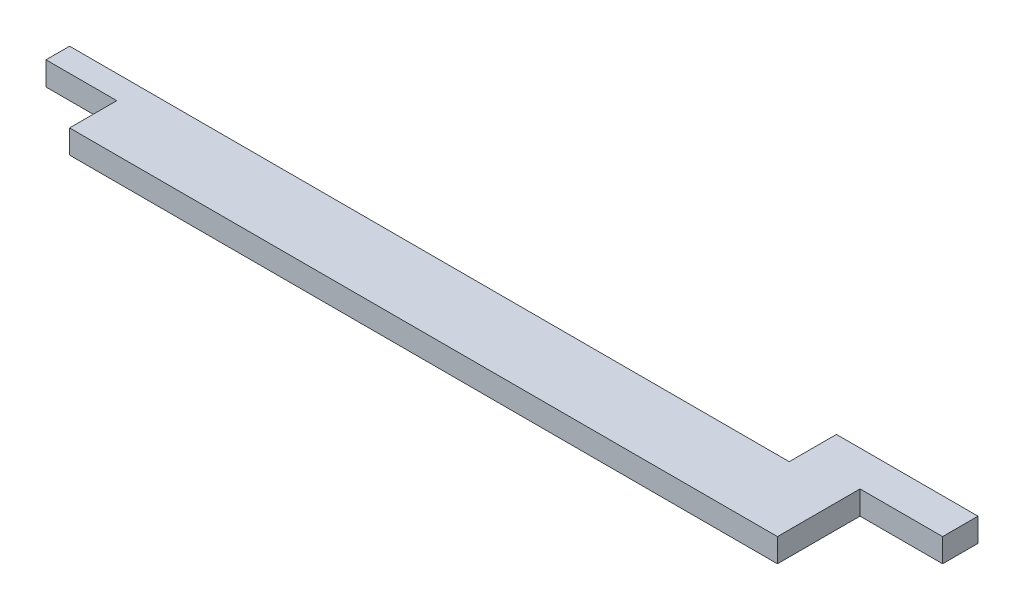
SolidWorks part; units mm, degrees
ref_plane "Front Plane" through (0, 0, 0) normal (0, 0, 1) x (1, 0, 0)
ref_plane "Top Plane" through (0, 0, 0) normal (0, 1, 0) x (1, 0, 0)
ref_plane "Right Plane" through (0, 0, 0) normal (1, 0, 0) x (0, 0, -1)
sketch "Sketch1" plane through (0, 0, 0) normal (0, 0, 1) x (1, 0, 0)
  line L1 (0, 2.54) -> (76.2, 2.54)
  line L2 (0, 2.54) -> (0, 0)
  line L3 (0, 0) -> (76.2, 0)
  line L4 (76.2, 2.54) -> (76.2, 0)
  point P4 (0, 0)
  dimension "D1" = 76.2
  dimension "D2" = 2.54
extrude "Boss-Extrude1" add sketch "Sketch1" along normal blind 7.62
sketch "Sketch3" plane through (0, 0, 0) normal (-1, 0, 0) x (0, 0, 1)
  line L0 (7.62, 0) -> (0, 0) construction
  line L1 (0, 2.54) -> (2.54, 2.54)
  line L2 (0, 2.54) -> (0, 0)
  line L3 (0, 0) -> (2.54, 0)
  line L4 (2.54, 2.54) -> (2.54, 0)
  line L5 (7.62, 2.54) -> (7.62, 0) construction
  dimension "D1" = 5.08
extrude "Boss-Extrude2" add sketch "Sketch3" along normal blind 7.62
sketch "Sketch4" plane through (0, 0, 0) normal (0, 0, -1) x (-1, 0, 0)
  line L0 (-76.2, 2.54) -> (7.62, 2.54) construction
  line L1 (-69.85, 2.54) -> (-85.09, 2.54)
  line L2 (-69.85, 2.54) -> (-69.85, 0)
  line L3 (-69.85, 0) -> (-85.09, 0)
  line L4 (-85.09, 2.54) -> (-85.09, 0)
  line L5 (-76.2, 0) -> (-76.2, 2.54) construction
  dimension "D1" = 2.54
  dimension "D2" = 15.24
  dimension "D3" = 6.35
extrude "Boss-Extrude3" add sketch "Sketch4" along normal blind 5.08
sketch "Sketch5" plane through (85.09, 0, 0) normal (1, 0, 0) x (0, 0, -1)
  line L0 (5.08, 0) -> (0, 0) construction
  line L1 (0, 2.54) -> (1.27, 2.54)
  line L2 (0, 2.54) -> (0, 0)
  line L3 (0, 0) -> (1.27, 0)
  line L4 (1.27, 2.54) -> (1.27, 0)
  dimension "D1" = 1.27
extrude "Cut-Extrude2" cut sketch "Sketch5" against normal up to surface (8.89 mm away) up to face at (76.2, 1.27, 3.81)
